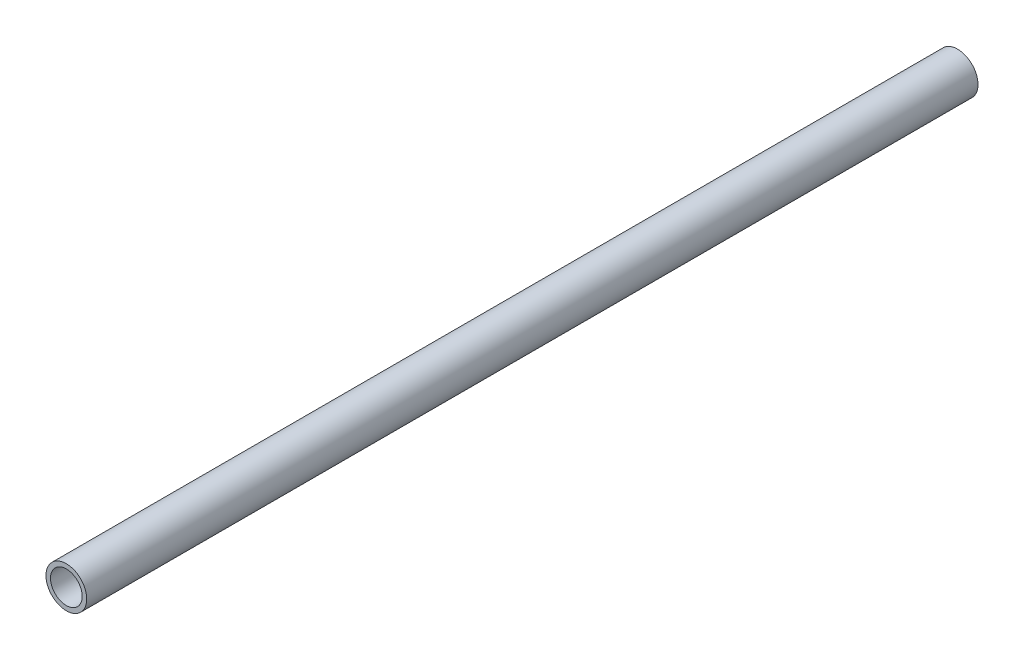
SolidWorks part; units mm, degrees
ref_plane "Front Plane" through (0, 0, 0) normal (0, 0, 1) x (1, 0, 0)
ref_plane "Top Plane" through (0, 0, 0) normal (0, 1, 0) x (1, 0, 0)
ref_plane "Right Plane" through (0, 0, 0) normal (1, 0, 0) x (0, 0, -1)
sketch "Sketch1" plane through (0, 0, 0) normal (0, 0, 1) x (1, 0, 0)
  circle A0 centre (0, 0) radius 9
  circle A1 centre (0, 0) radius 7
  dimension "D1" = 14
  dimension "D2" = 18
extrude "Boss-Extrude1" add sketch "Sketch1" along normal blind 393.37
